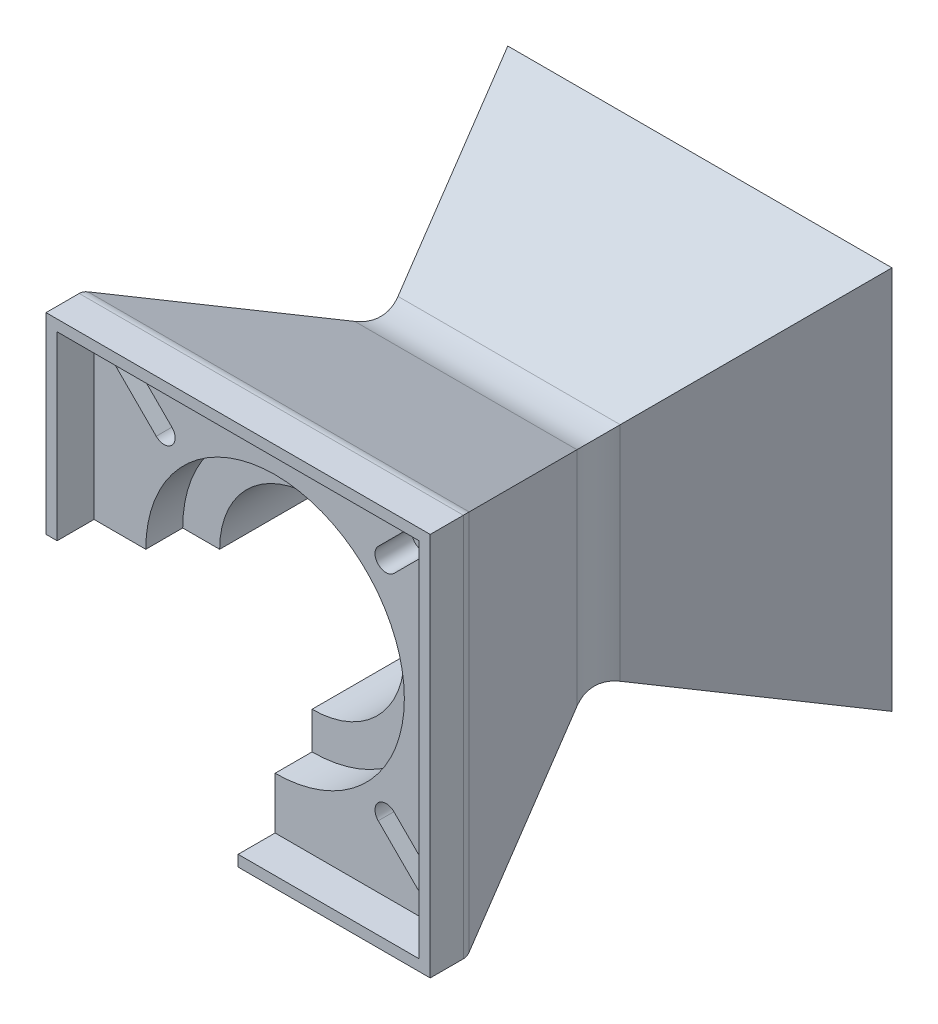
SolidWorks part; units mm, degrees
material "Cast Stainless Steel"
ref_plane "Front Plane" through (0, 0, 0) normal (0, 0, 1) x (1, 0, 0)
ref_plane "Top Plane" through (0, 0, 0) normal (0, 1, 0) x (1, 0, 0)
ref_plane "Right Plane" through (0, 0, 0) normal (1, 0, 0) x (0, 0, -1)
sketch "Sketch1" plane through (0, 0, 0) normal (0, 0, 1) x (1, 0, 0)
  line L1 (-52, 52) -> (52, 52)
  line L2 (-52, 52) -> (-52, -52)
  line L3 (-52, -52) -> (52, -52)
  line L4 (52, 52) -> (52, -52)
  line L5 (-52, 52) -> (52, -52) construction
  line L6 (-52, -52) -> (52, 52) construction
  circle A0 centre (0, 0) radius 25
  point P0 (0, 0)
  dimension "D3" = 50
  dimension "D1" = 104
  dimension "D2" = 104
extrude "Boss-Extrude1" add sketch "Sketch1" along normal blind 115
sketch "Sketch2" plane through (-52, 0, 0) normal (-1, 0, 0) x (0, 0, 1)
  line L0 (0, 52) -> (0, -52)
  line L1 (0, 52) -> (115, 52)
  line L2 (115, 52) -> (57.5, 27.5927)
  line L3 (57.5, 27.5927) -> (0, 52)
  line L4 (0, 0) -> (115, 0)
  line L5 (115, 52) -> (115, -52) construction
  line L6 (0, -52) -> (115, -52)
  line L7 (115, -52) -> (57.5, -27.5927)
  line L8 (57.5, -27.5927) -> (0, -52)
  dimension "D1" = 23
  dimension "D2" = 23
sketch "Sketch5" plane through (0, 52, 0) normal (0, 1, 0) x (1, 0, 0)
  line L0 (-52, 0) -> (-52, -115)
  line L1 (52, 0) -> (-52, 0) construction
  line L2 (-52, -115) -> (-27.5927, -57.5)
  line L3 (-27.5927, -57.5) -> (-52, 0)
  line L4 (0, 0) -> (0, -115)
  line L5 (52, -115) -> (-52, -115) construction
  line L6 (52, -115) -> (27.5927, -57.5)
  line L7 (27.5927, -57.5) -> (52, 0)
  line L8 (52, 0) -> (52, -115)
  line M6 (-52, 0) -> (-52, -115)
  line M8 (52, -115) -> (52, 0)
  dimension "D1" = 23
  dimension "D2" = 23
extrude "Cut-Extrude3" cut sketch "Sketch5" against normal blind 115 contours L7 L6 M8 | L2 L3 M6
extrude "Cut-Extrude4" cut sketch "Sketch2" against normal blind 115 contours L3 L2 L7 | L7 L8 L5
sketch "Sketch7" plane through (0, 0, 0) normal (0, 0, 1) x (1, 0, 0)
  circle A0 centre (0, 0) radius 35
  dimension "D1" = 70
extrude "Cut-Extrude5" cut sketch "Sketch7" along normal blind 10
sketch "Sketch8" plane through (0, 0, 115) normal (0, 0, 1) x (1, 0, 0)
  circle A0 centre (0, 0) radius 35
  dimension "D1" = 70
extrude "Cut-Extrude6" cut sketch "Sketch8" against normal blind 10
fillet "Fillet1" radius 15 4 edges at (-27.5927, 0, 57.5) (0, -27.5927, 57.5) (27.5927, 0, 57.5) (0, 27.5927, 57.5)
sketch "Sketch10" plane through (0, 0, 0) normal (0, 0, -1) x (-1, 0, 0)
  line L0 (0, 0) -> (0, -55.7)
  line L1 (0, -55.7) -> (0, 0)
  line L2 (0, 0) -> (59.4427, 0)
  arc A0 (0, -55.7) -> (59.4427, 0) centre (27.2425, -25.2046) ccw
  circle M1 centre (0, 0) radius 35
  line M3 (-52, -52) -> (52, -52)
  line M4 (52, -52) -> (52, 52)
extrude "Cut-Extrude7" cut sketch "Sketch10" against normal through all contours L2 L0 M1 M3 M4 | L2 L0 M1
sketch "Sketch13" plane through (0, 0, 115) normal (0, 0, 1) x (1, 0, 0)
  line L1 (-52, 0) -> (-52, 52)
  line L2 (-49, 52) -> (-49, 0)
  line L3 (-49, 52) -> (-49, 0)
  line L4 (-52, 52) -> (52, 52)
  line L5 (52, -52) -> (52, 52) construction
  line L6 (52, 52) -> (-52, 52) construction
  line L7 (52, 52) -> (52, -52)
  line L8 (52, -52) -> (0, -52)
  line L13 (0, -35) -> (0, -52) construction
  line L14 (-35, 0) -> (-52, 0) construction
  line L15 (0, -52) -> (0, -49)
  line L16 (-52, 0) -> (-49, 0)
  line L18 (-49, 49) -> (-49, 3)
  line L19 (-49, 3) -> (-37.8814, 3)
  line L20 (3, -37.8814) -> (3, -49)
  line L21 (3, -49) -> (49, -49)
  line L22 (49, -49) -> (49, 49)
  line L23 (49, 49) -> (-49, 49)
  line L24 (-49, 49) -> (-49, 0)
  line L27 (0, -49) -> (49, -49)
  line L28 (49, -49) -> (49, 49)
  line L29 (49, 49) -> (-49, 49)
  arc A3 (3, -37.8814) -> (-37.8814, 3) centre (0, 0) ccw
  dimension "D1" = 3
  dimension "D2" = 3
extrude "Boss-Extrude2" add sketch "Sketch13" along normal blind 10 contours L16 L1 L4 L7 L8 L15 L27 L28 L29 L24
sketch "Sketch14" plane through (0, 0, 115) normal (0, 0, 1) x (1, 0, 0)
  line L0 (0, 0) -> (-49, 49) construction
  line L1 (-40.6586, 40.6586) -> (-30.052, 30.052) construction
  line L2 (-38.5373, 42.78) -> (-27.9307, 32.1734)
  line L3 (-42.78, 38.5373) -> (-32.1734, 27.9307)
  line L4 (40.6586, 40.6586) -> (30.052, 30.052) construction
  line L5 (42.78, 38.5373) -> (32.1734, 27.9307)
  line L6 (38.5373, 42.78) -> (27.9307, 32.1734)
  line L7 (40.6586, -40.6586) -> (30.052, -30.052) construction
  line L8 (38.5373, -42.78) -> (27.9307, -32.1734)
  line L9 (42.78, -38.5373) -> (32.1734, -27.9307)
  line L16 (-40.6586, -40.6586) -> (-30.052, -30.052) construction
  line L17 (-42.78, -38.5373) -> (-32.1734, -27.9307)
  line L18 (-38.5373, -42.78) -> (-27.9307, -32.1734)
  line L19 (-40.6586, -40.6586) -> (-30.052, -30.052) construction
  line L20 (-42.78, -38.5373) -> (-32.1734, -27.9307)
  line L21 (-38.5373, -42.78) -> (-27.9307, -32.1734)
  arc A0 (-38.5373, 42.78) -> (-42.78, 38.5373) centre (-40.6586, 40.6586) ccw
  arc A1 (-32.1734, 27.9307) -> (-27.9307, 32.1734) centre (-30.052, 30.052) ccw
  arc A2 (42.78, 38.5373) -> (38.5373, 42.78) centre (40.6586, 40.6586) ccw
  arc A3 (27.9307, 32.1734) -> (32.1734, 27.9307) centre (30.052, 30.052) ccw
  arc A4 (38.5373, -42.78) -> (42.78, -38.5373) centre (40.6586, -40.6586) ccw
  arc A5 (32.1734, -27.9307) -> (27.9307, -32.1734) centre (30.052, -30.052) ccw
  arc A12 (-42.78, -38.5373) -> (-38.5373, -42.78) centre (-40.6586, -40.6586) ccw
  arc A13 (-27.9307, -32.1734) -> (-32.1734, -27.9307) centre (-30.052, -30.052) ccw
  point P6 (-35.3553, 35.3553)
  point P13 (-35.3553, -35.3553)
  point P16 (35.3553, 35.3553)
  point P23 (35.3553, -35.3553)
  point P28 (0, 0)
  point P35 (0, 0)
  point P43 (-35.3553, -35.3553)
  point P50 (-35.3553, -35.3553)
  dimension "D2" = 3
  dimension "D1" = 15
  dimension "D3" = 50
  dimension "D4" = 4
extrude "Cut-Extrude8" cut sketch "Sketch14" against normal blind 10
fillet "Fillet2" radius 5 4 edges at (26, -52, 115) (52, 0, 115) (0, 52, 115) (-52, 26, 115)
